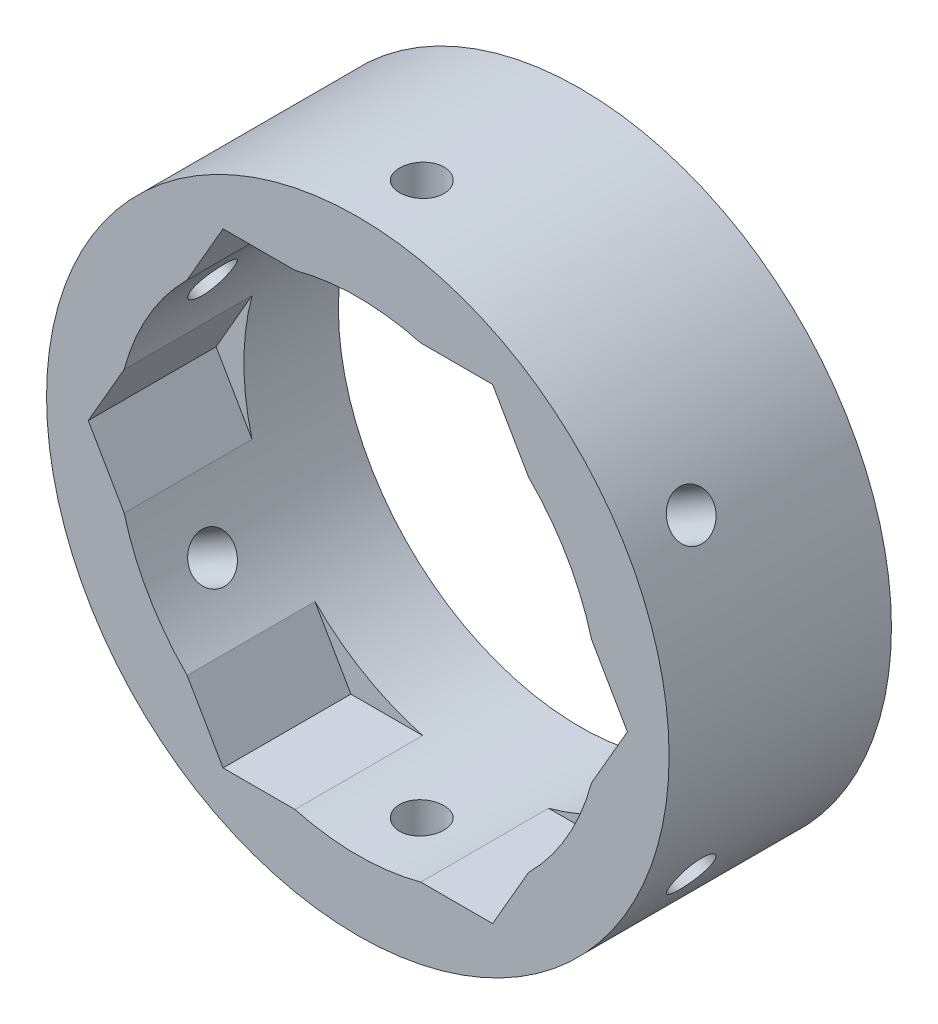
SolidWorks part; units mm, degrees
ref_plane "Front Plane" through (0, 0, 0) normal (0, 0, 1) x (1, 0, 0)
ref_plane "Top Plane" through (0, 0, 0) normal (0, 1, 0) x (1, 0, 0)
ref_plane "Right Plane" through (0, 0, 0) normal (1, 0, 0) x (0, 0, -1)
sketch "Sketch1" plane through (0, 0, 0) normal (0, 0, 1) x (1, 0, 0)
  circle A0 centre (0, 0) radius 14
extrude "Boss-Extrude1" add sketch "Sketch1" along normal blind 10
sketch "Sketch2" plane through (0, 0, 10) normal (0, 0, 1) x (1, 0, 0)
  circle A0 centre (0, 0) radius 10.875
  dimension "D1" = 21.75
extrude "Cut-Extrude1" cut sketch "Sketch2" against normal up to next
sketch "Sketch3" plane through (0, 0, 10) normal (0, 0, 1) x (1, 0, 0)
  line L1 (12.1244, 0) -> (6.0622, 10.5)
  line L2 (6.0622, 10.5) -> (-6.0622, 10.5)
  line L3 (-6.0622, 10.5) -> (-12.1244, 0)
  line L4 (-12.1244, 0) -> (-6.0622, -10.5)
  line L5 (-6.0622, -10.5) -> (6.0622, -10.5)
  line L6 (6.0622, -10.5) -> (12.1244, 0)
  circle A0 centre (0, 0) radius 10.5 construction
  point P1 (0, 0)
extrude "Cut-Extrude2" cut sketch "Sketch3" against normal blind 5.75
sketch "Sketch4" plane through (0, 10.5, 0) normal (0, -1, 0) x (-1, 0, 0)
  line L0 (6.0622, -7.125) -> (-6.0622, -7.125) construction
  line L1 (6.0622, -4.25) -> (6.0622, -10) construction
  line L2 (-6.0622, -4.25) -> (-6.0622, -10) construction
  circle A0 centre (0, -7.125) radius 1
extrude "Cut-Extrude3" cut sketch "Sketch4" against normal up to next
sketch "Sketch5" plane through (9.0933, 5.25, 0) normal (-0.866, -0.5, 0) x (0, 0, 1)
  line L0 (7.125, 6.0622) -> (7.125, -6.0622) construction
  line L1 (4.25, 6.0622) -> (10, 6.0622) construction
  line L2 (4.25, -6.0622) -> (10, -6.0622) construction
  circle A0 centre (7.125, 0) radius 1
extrude "Cut-Extrude4" cut sketch "Sketch5" against normal up to next
sketch "Sketch6" plane through (9.0933, -5.25, 0) normal (-0.866, 0.5, 0) x (0, 0, 1)
  line L0 (7.125, 6.0622) -> (7.125, -6.0622) construction
  line L1 (4.25, 6.0622) -> (10, 6.0622) construction
  line L2 (4.25, -6.0622) -> (10, -6.0622) construction
  circle A0 centre (7.125, 0) radius 1
extrude "Cut-Extrude5" cut sketch "Sketch6" against normal up to next
sketch "Sketch7" plane through (0, -10.5, 0) normal (0, 1, 0) x (1, 0, 0)
  line L0 (-6.0622, -7.125) -> (6.0622, -7.125) construction
  line L1 (-6.0622, -4.25) -> (-6.0622, -10) construction
  line L2 (6.0622, -4.25) -> (6.0622, -10) construction
  circle A0 centre (0, -7.125) radius 1
extrude "Cut-Extrude6" cut sketch "Sketch7" against normal up to next
sketch "Sketch8" plane through (-9.0933, -5.25, 0) normal (0.866, 0.5, 0) x (0, 0, -1)
  line L0 (-7.125, 6.0622) -> (-7.125, -6.0622) construction
  line L1 (-4.25, 6.0622) -> (-10, 6.0622) construction
  line L2 (-4.25, -6.0622) -> (-10, -6.0622) construction
  circle A0 centre (-7.125, 0) radius 1
extrude "Cut-Extrude7" cut sketch "Sketch8" against normal up to next
sketch "Sketch9" plane through (-9.0933, 5.25, 0) normal (0.866, -0.5, 0) x (0, 0, -1)
  line L0 (-7.125, 6.0622) -> (-7.125, -6.0622) construction
  line L1 (-4.25, 6.0622) -> (-10, 6.0622) construction
  line L2 (-4.25, -6.0622) -> (-10, -6.0622) construction
  circle A0 centre (-7.125, 0) radius 1
extrude "Cut-Extrude8" cut sketch "Sketch9" against normal up to next
